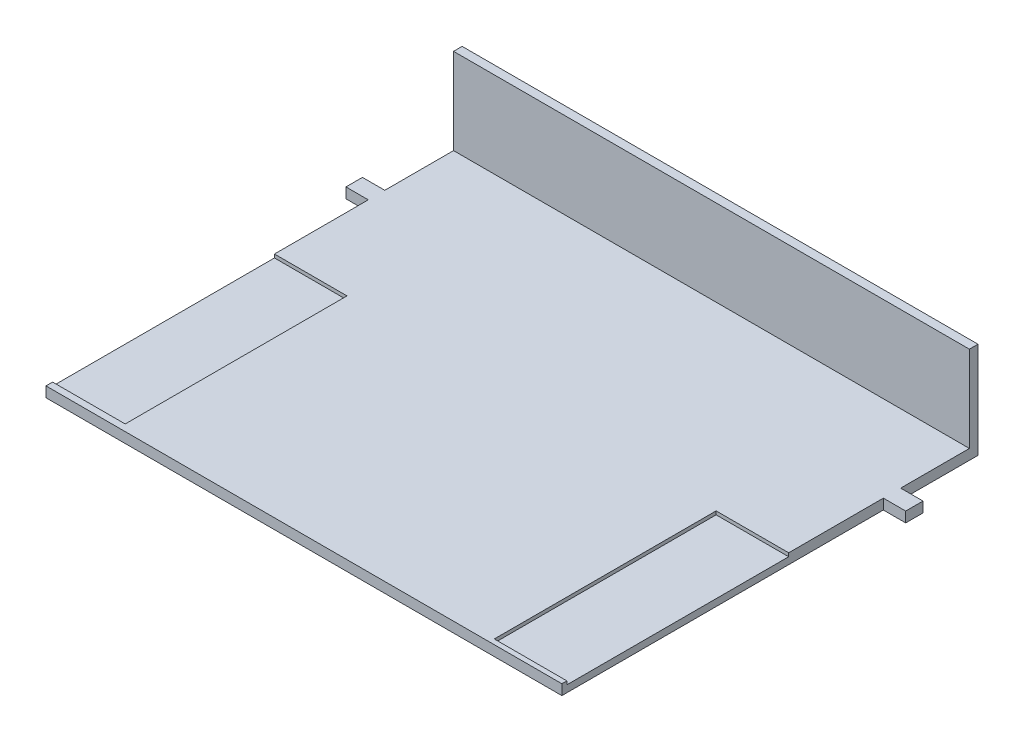
SolidWorks part; units mm, degrees
ref_plane "Front Plane" through (0, 0, 0) normal (0, 0, 1) x (1, 0, 0)
ref_plane "Top Plane" through (0, 0, 0) normal (0, 1, 0) x (1, 0, 0)
ref_plane "Right Plane" through (0, 0, 0) normal (1, 0, 0) x (0, 0, -1)
sketch "Sketch1" plane through (0, 0, 0) normal (0, 0, 1) x (1, 0, 0)
  line L1 (0, 0) -> (150, 0)
  line L2 (0, 0) -> (0, 3)
  line L3 (0, 3) -> (150, 3)
  line L4 (150, 0) -> (150, 3)
  dimension "D1" = 3
  dimension "D2" = 150
extrude "Boss-Extrude1" add sketch "Sketch1" along normal blind 121 contours L2 L1 L4 L3
ref_plane "Plane1" through (150, 3, 121) normal (0, 0, -1) x (-1, 0, 0)
sketch "Sketch3" plane through (0, 3, 0) normal (0, 1, 0) x (1, 0, 0)
  line L0 (0, -119.0747) -> (21.1, -119.0747)
  line L1 (0, -121) -> (0, 0) construction
  line L2 (21.1, -119.0747) -> (21.1, -54.5747)
  line L3 (21.1, -54.5747) -> (0, -54.5747)
  line L4 (0, -54.5747) -> (0, -119.0747)
extrude "Cut-Extrude1" cut sketch "Sketch3" against normal blind 1 contours L4 L0 L2 L3
sketch "Sketch4" plane through (0, 3, 0) normal (0, 1, 0) x (1, 0, 0)
  line L0 (128.9, -55.0483) -> (150, -55.0483)
  line L1 (150, -121) -> (150, 0) construction
  line L2 (150, -119.5483) -> (128.9, -119.5483)
  line L3 (150, -119.5483) -> (150, -55.0483)
  line L4 (128.9, -119.5483) -> (128.9, -55.0483)
extrude "Cut-Extrude2" cut sketch "Sketch4" against normal blind 1
ref_plane "Plane2" through (150, 3, 0) normal (0, 0, -1) x (-1, 0, 0)
sketch "Sketch6" plane through (0, 0, 0) normal (0, 1, 0) x (1, 0, 0)
  line L0 (0, -22.4873) -> (-6.5, -22.4873)
  line L1 (0, -54.5747) -> (0, 0) construction
  line L2 (-6.5, -22.4873) -> (-6.5, -27.2873)
  line L3 (-6.5, -27.2873) -> (0, -27.2873)
  line L4 (0, -27.2873) -> (0, -22.4873)
  line L5 (150, -22.4873) -> (156.5, -22.4873)
  line L6 (150, -121) -> (150, 0) construction
  line L7 (156.5, -22.4873) -> (156.5, -27.2873)
  line L8 (156.5, -27.2873) -> (150, -27.2873)
  line L9 (150, -27.2873) -> (150, -22.4873)
extrude "Boss-Extrude5" add sketch "Sketch6" along normal blind 3 contours L4 L0 L2 L3
sketch "Sketch9" plane through (0, 3, 0) normal (0, 1, 0) x (1, 0, 0)
  line L1 (150, -55.0483) -> (150, 0) construction
  line L2 (150, -22.4873) -> (150, -27.5241)
  line L3 (150, -27.5241) -> (156.5, -27.5241)
  line L4 (156.5, -27.5241) -> (156.5, -22.4873)
  line L5 (156.5, -22.4873) -> (150, -22.4873)
extrude "Boss-Extrude7" add sketch "Sketch9" against normal blind 3
sketch "Sketch10" plane through (0, 0, 0) normal (0, 0, -1) x (-1, 0, 0)
  line L0 (-150, 3) -> (-150, 28)
  line L1 (-150, 28) -> (0, 28)
  line L2 (0, 28) -> (0, 3)
  line L3 (-150, 3) -> (0, 3)
extrude "Boss-Extrude8" add sketch "Sketch10" against normal blind 2.5
sketch "Sketch12" plane through (0, 3, 0) normal (0, 1, 0) x (1, 0, 0)
  circle A0 centre (126.827, -57.5427) radius 1.5
  circle A1 centre (126.827, -82.3903) radius 1.5
  circle A2 centre (126.827, -105.463) radius 1.5
  circle A3 centre (22.8222, -57.5427) radius 1.5
  circle A4 centre (22.8222, -82.3903) radius 1.5
  circle A5 centre (22.8222, -105.463) radius 1.5
  circle A7 centre (71.0208, -116.9209) radius 3
  circle A8 centre (31.294, -97.8274) radius 3
  circle A9 centre (31.294, -73.0679) radius 3
  circle A10 centre (120.5816, -73.0679) radius 3
  circle A11 centre (120.5816, -97.8274) radius 3
